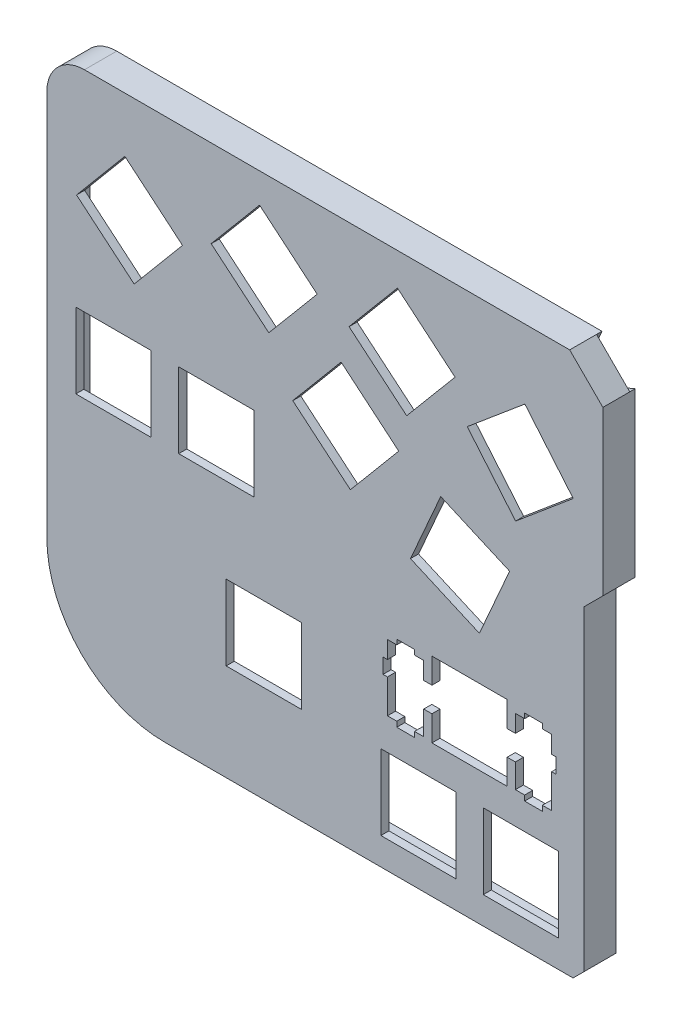
SolidWorks part; units mm, degrees
ref_plane "前视基准面" through (0, 0, 0) normal (0, 0, 1) x (1, 0, 0)
ref_plane "上视基准面" through (0, 0, 0) normal (0, 1, 0) x (1, 0, 0)
ref_plane "右视基准面" through (0, 0, 0) normal (1, 0, 0) x (0, 0, -1)
other "Configuration Table"
sketch "Model" plane through (0, 0, 0) normal (0, 0, 1) x (1, 0, 0)
  line L0 (37.6582, 36.5304) -> (26.9341, 27.5319)
  line L1 (26.9341, 27.5319) -> (35.9327, 16.8078)
  line L2 (35.9327, 16.8078) -> (46.6568, 25.8063)
  line L3 (46.6568, 25.8063) -> (37.6582, 36.5304)
  line L4 (13.9373, 43.3698) -> (4.9388, 32.6457)
  line L5 (4.9388, 32.6457) -> (15.6628, 23.6471)
  line L6 (15.6628, 23.6471) -> (24.6614, 34.3712)
  line L7 (24.6614, 34.3712) -> (13.9373, 43.3698)
  line L8 (-11.7243, 43.9125) -> (-20.7229, 33.1884)
  line L9 (-20.7229, 33.1884) -> (-9.9988, 24.1898)
  line L10 (-9.9988, 24.1898) -> (-1.0002, 34.9139)
  line L11 (-1.0002, 34.9139) -> (-11.7243, 43.9125)
  line L12 (-36.7823, 39.2378) -> (-45.7809, 28.5137)
  line L13 (-45.7809, 28.5137) -> (-35.0568, 19.5151)
  line L14 (-35.0568, 19.5151) -> (-26.0582, 30.2392)
  line L15 (-26.0582, 30.2392) -> (-36.7823, 39.2378)
  line L16 (34.8184, 8.1678) -> (22.0001, 13.7955)
  line L17 (22.0001, 13.7955) -> (16.3723, 0.9773)
  line L18 (16.3723, 0.9773) -> (29.1906, -4.6505)
  line L19 (29.1906, -4.6505) -> (34.8184, 8.1678)
  line L20 (3.4563, 26.2055) -> (-5.5423, 15.4814)
  line L21 (-5.5423, 15.4814) -> (5.1818, 6.4828)
  line L22 (5.1818, 6.4828) -> (14.1804, 17.2069)
  line L23 (14.1804, 17.2069) -> (3.4563, 26.2055)
  line L24 (10.8632, -32.4107) -> (24.8625, -32.4107)
  line L25 (24.8625, -32.4107) -> (24.8625, -46.41)
  line L26 (24.8625, -46.41) -> (10.8632, -46.41)
  line L27 (10.8632, -46.41) -> (10.8632, -32.4107)
  line L28 (29.9135, -32.4107) -> (43.9128, -32.4107)
  line L29 (43.9128, -32.4107) -> (43.9128, -46.41)
  line L30 (43.9128, -46.41) -> (29.9135, -46.41)
  line L31 (29.9135, -46.41) -> (29.9135, -32.4107)
  line L32 (20.3636, -17.4315) -> (18.8376, -17.4315)
  line L33 (18.8376, -17.4315) -> (18.8376, -14.2015)
  line L34 (18.8376, -14.2015) -> (17.1126, -14.2015)
  line L35 (17.1126, -14.2015) -> (17.1126, -13.2821)
  line L36 (17.1126, -13.2821) -> (13.8136, -13.2821)
  line L37 (13.8136, -13.2821) -> (13.8136, -14.2015)
  line L38 (13.8136, -14.2015) -> (12.0868, -14.2015)
  line L39 (12.0868, -14.2015) -> (12.0868, -17.4315)
  line L40 (12.0868, -17.4315) -> (11.2627, -17.4315)
  line L41 (11.2627, -17.4315) -> (11.2627, -20.2317)
  line L42 (11.2627, -20.2317) -> (12.0868, -20.2317)
  line L43 (12.0868, -20.2317) -> (12.0868, -26.5018)
  line L44 (12.0868, -26.5018) -> (13.8136, -26.5018)
  line L45 (13.8136, -26.5018) -> (13.8136, -27.4816)
  line L46 (13.8136, -27.4816) -> (17.1126, -27.4816)
  line L47 (17.1126, -27.4816) -> (17.1126, -26.5018)
  line L48 (17.1126, -26.5018) -> (18.8376, -26.5018)
  line L49 (18.8376, -26.5018) -> (18.8376, -22.0315)
  line L50 (18.8376, -22.0315) -> (20.3636, -22.0315)
  line L51 (20.3636, -22.0315) -> (20.3636, -26.7319)
  line L52 (20.3636, -26.7319) -> (34.3626, -26.7319)
  line L53 (34.3626, -26.7319) -> (34.3626, -22.0315)
  line L54 (34.3626, -22.0315) -> (35.8886, -22.0315)
  line L55 (35.8886, -22.0315) -> (35.8886, -26.5018)
  line L56 (35.8886, -26.5018) -> (37.6136, -26.5018)
  line L57 (37.6136, -26.5018) -> (37.6136, -27.4816)
  line L58 (37.6136, -27.4816) -> (40.9126, -27.4816)
  line L59 (40.9126, -27.4816) -> (40.9126, -26.5018)
  line L60 (40.9126, -26.5018) -> (42.6376, -26.5018)
  line L61 (42.6376, -26.5018) -> (42.6376, -20.2317)
  line L62 (42.6376, -20.2317) -> (43.4636, -20.2317)
  line L63 (43.4636, -20.2317) -> (43.4636, -17.4315)
  line L64 (43.4636, -17.4315) -> (42.6376, -17.4315)
  line L65 (42.6376, -17.4315) -> (42.6376, -14.2015)
  line L66 (42.6376, -14.2015) -> (40.9126, -14.2015)
  line L67 (40.9126, -14.2015) -> (40.9126, -13.2821)
  line L68 (40.9126, -13.2821) -> (37.6136, -13.2821)
  line L69 (37.6136, -13.2821) -> (37.6136, -14.2015)
  line L70 (37.6136, -14.2015) -> (35.8886, -14.2015)
  line L71 (35.8886, -14.2015) -> (35.8886, -17.4315)
  line L72 (35.8886, -17.4315) -> (34.3626, -17.4315)
  line L73 (34.3626, -17.4315) -> (34.3626, -12.7325)
  line L74 (34.3626, -12.7325) -> (20.3636, -12.7325)
  line L75 (20.3636, -12.7325) -> (20.3636, -17.4315)
  line L76 (-45.908, 10.3811) -> (-31.9087, 10.3811)
  line L77 (-31.9087, 10.3811) -> (-31.9087, -3.6182)
  line L78 (-31.9087, -3.6182) -> (-45.908, -3.6182)
  line L79 (-45.908, -3.6182) -> (-45.908, 10.3811)
  line L80 (-26.7581, 10.3252) -> (-12.7588, 10.3252)
  line L81 (-12.7588, 10.3252) -> (-12.7588, -3.6741)
  line L82 (-12.7588, -3.6741) -> (-26.7581, -3.6741)
  line L83 (-26.7581, -3.6741) -> (-26.7581, 10.3252)
  line L84 (45.9993, 49.4346) -> (-44.303, 49.4346)
  line L85 (-51.303, 42.4346) -> (-51.303, -29.4876)
  line L86 (-29.303, -51.4876) -> (48.6287, -51.4876)
  line L87 (48.6287, -51.4876) -> (48.6287, 9.3281)
  line L88 (48.6287, 9.3281) -> (52.1789, 12.8783)
  line L89 (52.1789, 12.8783) -> (52.1789, 43.255)
  line L90 (52.1789, 43.255) -> (45.9993, 49.4346)
  line L91 (-17.9323, -19.4717) -> (-3.933, -19.4717)
  line L92 (-3.933, -19.4717) -> (-3.933, -33.471)
  line L93 (-3.933, -33.471) -> (-17.9323, -33.471)
  line L94 (-17.9323, -33.471) -> (-17.9323, -19.4717)
  circle A0 centre (-10.9326, -26.4713) radius 17
  arc A1 (-44.303, 49.4346) -> (-51.303, 42.4346) centre (-44.303, 42.4346) ccw
  arc A2 (-51.303, -29.4876) -> (-29.303, -51.4876) centre (-29.303, -29.4876) ccw
extrude "凸台-拉伸1" add sketch "Model" along normal blind 1.5 contours L85 A2 L86 L87 L88 L89 L90 L84 A1 L82 L83 L80 L81 L78 L79 L76 L77 L30 L31 L28 L29 L26 L27 L24 L25 L3 L2 L1 L0 L7 L6 L5 L4 L11 L10 L9 L8 L15 L14 L13 L12 L19 | A0 L93 L94 L91 L92
sketch "草图1" plane through (0, 0, 0) normal (0, 0, -1) x (-1, 0, 0)
  line L0 (44.303, 46.4346) -> (-44.7567, 46.4346)
  line L1 (-44.7567, 46.4346) -> (-49.1789, 42.0124)
  line L2 (-49.1789, 42.0124) -> (-49.1789, 14.1209)
  line L3 (-49.1789, 14.1209) -> (-45.6287, 10.5707)
  line L4 (-45.6287, 10.5707) -> (-45.6287, -48.4876)
  line L5 (-45.6287, -48.4876) -> (29.303, -48.4876)
  line L6 (48.303, -29.4876) -> (48.303, 42.4346)
  line L7 (51.303, -29.4876) -> (51.303, 42.4346)
  line L8 (44.303, 49.4346) -> (-45.9993, 49.4346)
  line L9 (-45.9993, 49.4346) -> (-52.1789, 43.255)
  line L10 (-52.1789, 43.255) -> (-52.1789, 12.8783)
  line L11 (-52.1789, 12.8783) -> (-48.6287, 9.3281)
  line L12 (-48.6287, 9.3281) -> (-48.6287, -51.4876)
  line L13 (-48.6287, -51.4876) -> (29.303, -51.4876)
  line L14 (51.303, -29.4876) -> (51.303, 42.4346)
  line L15 (44.303, 49.4346) -> (-45.9993, 49.4346)
  line L16 (-45.9993, 49.4346) -> (-52.1789, 43.255)
  line L17 (-52.1789, 43.255) -> (-52.1789, 12.8783)
  line L18 (-52.1789, 12.8783) -> (-48.6287, 9.3281)
  line L19 (-48.6287, 9.3281) -> (-48.6287, -51.4876)
  line L20 (-48.6287, -51.4876) -> (29.303, -51.4876)
  arc A0 (29.303, -48.4876) -> (48.303, -29.4876) centre (29.303, -29.4876) ccw
  arc A1 (48.303, 42.4346) -> (44.303, 46.4346) centre (44.303, 42.4346) ccw
  arc A2 (51.303, 42.4346) -> (44.303, 49.4346) centre (44.303, 42.4346) ccw
  arc A3 (29.303, -51.4876) -> (51.303, -29.4876) centre (29.303, -29.4876) ccw
  arc A4 (51.303, 42.4346) -> (44.303, 49.4346) centre (44.303, 42.4346) ccw
  arc A5 (29.303, -51.4876) -> (51.303, -29.4876) centre (29.303, -29.4876) ccw
  dimension "D1" = 0
  dimension "D2" = 3
extrude "凸台-拉伸2" add sketch "草图1" along normal blind 3.5
chamfer "倒角1" distance 2 angle 45 1 edges at (48.6287, -51.4876, -1)
sketch "草图2" plane through (0, 0, -3.5) normal (0, 0, -1) x (-1, 0, 0)
  line L51 (-52.1789, 43.255) -> (-50.2789, 42.468)
  line L52 (-45.9993, 49.4346) -> (-45.2123, 47.5346)
  line L59 (49.403, -29.4876) -> (49.403, 42.4346)
  line L60 (-45.8417, -49.5876) -> (29.303, -49.5876)
  line L61 (-46.7287, -48.7006) -> (-45.8417, -49.5876)
  line L62 (-46.7287, 10.1151) -> (-46.7287, -48.7006)
  line L63 (-50.2789, 13.6653) -> (-46.7287, 10.1151)
  line L64 (-50.2789, 42.468) -> (-50.2789, 13.6653)
  line L65 (-45.2123, 47.5346) -> (-50.2789, 42.468)
  line L66 (44.303, 47.5346) -> (-45.2123, 47.5346)
  line L67 (49.403, -29.4876) -> (49.403, 42.4346)
  line L68 (-45.8417, -49.5876) -> (29.303, -49.5876)
  line L69 (-46.7287, -48.7006) -> (-45.8417, -49.5876)
  line L70 (-46.7287, 10.1151) -> (-46.7287, -48.7006)
  line L71 (-50.2789, 13.6653) -> (-46.7287, 10.1151)
  line L72 (-50.2789, 42.468) -> (-50.2789, 13.6653)
  line L74 (44.303, 47.5346) -> (-45.2123, 47.5346)
  line L75 (-48.6287, 9.3281) -> (-48.6287, -49.4876)
  line L76 (-48.6287, -49.4876) -> (-46.6287, -51.4876)
  line L77 (-46.6287, -51.4876) -> (29.303, -51.4876)
  line L78 (51.303, -29.4876) -> (51.303, 42.4346)
  line L79 (44.303, 49.4346) -> (-45.9993, 49.4346)
  line L80 (-45.9993, 49.4346) -> (-52.1789, 43.255)
  line L81 (-52.1789, 43.255) -> (-52.1789, 12.8783)
  line L82 (-52.1789, 12.8783) -> (-48.6287, 9.3281)
  line L83 (-48.6287, 9.3281) -> (-48.6287, -49.4876)
  line L84 (-48.6287, -49.4876) -> (-46.6287, -51.4876)
  line L85 (-46.6287, -51.4876) -> (29.303, -51.4876)
  line L86 (51.303, -29.4876) -> (51.303, 42.4346)
  line L87 (44.303, 49.4346) -> (-45.9993, 49.4346)
  line L89 (-52.1789, 43.255) -> (-52.1789, 12.8783)
  line L90 (-52.1789, 12.8783) -> (-48.6287, 9.3281)
  arc A6 (49.403, 42.4346) -> (44.303, 47.5346) centre (44.303, 42.4346) ccw
  arc A7 (29.303, -49.5876) -> (49.403, -29.4876) centre (29.303, -29.4876) ccw
  arc A8 (49.403, 42.4346) -> (44.303, 47.5346) centre (44.303, 42.4346) ccw
  arc A9 (29.303, -49.5876) -> (49.403, -29.4876) centre (29.303, -29.4876) ccw
  arc A10 (29.303, -51.4876) -> (51.303, -29.4876) centre (29.303, -29.4876) ccw
  arc A11 (51.303, 42.4346) -> (44.303, 49.4346) centre (44.303, 42.4346) ccw
  arc A12 (29.303, -51.4876) -> (51.303, -29.4876) centre (29.303, -29.4876) ccw
  arc A13 (51.303, 42.4346) -> (44.303, 49.4346) centre (44.303, 42.4346) ccw
  dimension "D1" = 1.9
  dimension "D2" = 0
extrude "凸台-拉伸3" add sketch "草图2" along normal blind 1
